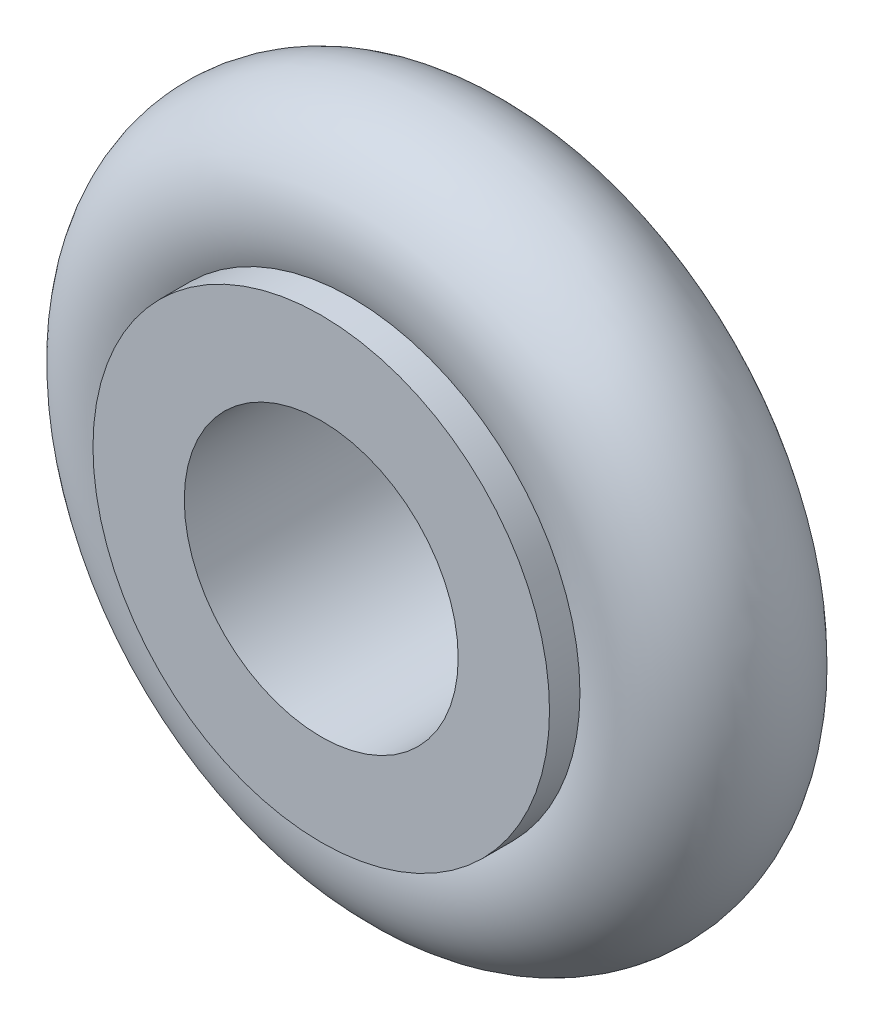
SolidWorks part; units mm, degrees
ref_plane "Alzado" through (0, 0, 0) normal (0, 0, 1) x (1, 0, 0)
ref_plane "Planta" through (0, 0, 0) normal (0, 1, 0) x (1, 0, 0)
ref_plane "Vista lateral" through (0, 0, 0) normal (1, 0, 0) x (0, 0, -1)
sketch "Croquis1" plane through (0, 0, 0) normal (1, 0, 0) x (0, 0, -1)
  line L0 (6.2271, 0) -> (-6.2271, 0) construction
  line L1 (0, 21.5) -> (0, -21.5) construction
  line L2 (-1.9, 0) -> (-1.9, 3.75)
  line L3 (-1.9, 3.75) -> (-1.4, 3.75)
  line L4 (-1.4, 3.75) -> (-1.05, 2.7778)
  line L5 (-1.05, 2.7778) -> (1.05, 2.7778)
  line L6 (1.4, 3.75) -> (1.05, 2.7778)
  line L7 (1.9, 3.75) -> (1.4, 3.75)
  line L8 (1.9, 0) -> (1.9, 3.75)
  line L9 (-1.9, 0) -> (1.9, 0)
  point P4 (0, 0)
  point P8 (0, 0)
  point P18 (0, 2.7778)
  dimension "D1" = 7.5
  dimension "D2" = 3.8
  dimension "D3" = 19.8
  dimension "D4" = 2.1
  dimension "D5" = 0.5
revolve "Revolución1" add sketch "Croquis1" angle 360 about L0
sketch "Croquis5" plane through (0, 0, 0) normal (1, 0, 0) x (0, 0, -1)
  line L0 (-1.05, 2.7778) -> (-1.4, 3.75) construction
  line L1 (-9.0932, 0) -> (9.0932, 0) construction
  circle A0 centre (0, 4.2896) radius 1.5
  point P9 (0, 0)
  dimension "D1" = 3
revolve "Revolución2" add sketch "Croquis5" angle 360 about L1
sketch "Croquis6" plane through (0, 0, 1.9) normal (0, 0, 1) x (1, 0, 0)
  circle A0 centre (0, 0) radius 2.25
  dimension "D1" = 4.5
extrude "Cortar-Extruir3" cut sketch "Croquis6" against normal up to next (3.8 mm away)
sketch "Croquis7" plane through (0, 0, 0) normal (1, 0, 0) x (0, 0, -1)
  line L2 (-1.9, 2.25) -> (1.9, 2.25) construction
  line L3 (-1.05, 2.7778) -> (1.05, 2.7778) construction
  dimension "D1" = 0.5278
sketch "Croquis8" plane through (0, 0, 0) normal (0, 0, 1) x (1, 0, 0)
  circle A0 centre (0, 0) radius 4.2896 construction
  circle A1 centre (0, 0) radius 5.7896
  circle A2 centre (0, 0) radius 5.7896 construction
  dimension "D1" = 8.5791
  dimension "D2" = 11.5791
